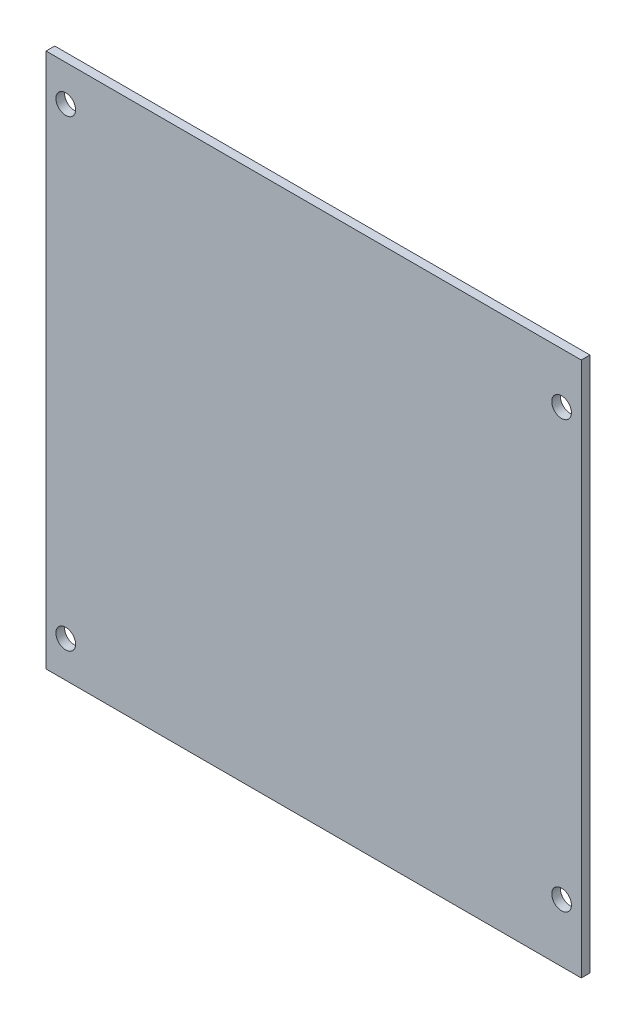
SolidWorks part; units mm, degrees
material "FR4"
ref_plane "Front Plane" through (0, 0, 0) normal (0, 0, 1) x (1, 0, 0)
ref_plane "Top Plane" through (0, 0, 0) normal (0, 1, 0) x (1, 0, 0)
ref_plane "Right Plane" through (0, 0, 0) normal (1, 0, 0) x (0, 0, -1)
sketch "Sketch1" plane through (0, 0, 0) normal (0, 0, 1) x (1, 0, 0)
  line L1 (46.25, -46.25) -> (-46.25, -46.25)
  line L2 (46.25, -46.25) -> (46.25, 46.25)
  line L3 (46.25, 46.25) -> (-46.25, 46.25)
  line L4 (-46.25, -46.25) -> (-46.25, 46.25)
  line L5 (46.25, -46.25) -> (-46.25, 46.25) construction
  line L6 (46.25, 46.25) -> (-46.25, -46.25) construction
  point P0 (0, 0)
  dimension "D1" = 92.5
  dimension "D2" = 92.5
extrude "Boss-Extrude1" add sketch "Sketch1" along normal blind 1.5
ref_plane "Plane1" through (0, 0, 0) normal (0, 1, 0) x (1, 0, 0)
ref_plane "Plane2" through (0, 0, 0) normal (1, 0, 0) x (0, 0, -1)
sketch "Sketch5" plane through (0, 0, 1.5) normal (0, 0, 1) x (1, 0, 0)
  line L0 (42.85, -36.2) -> (42.85, 37.5) construction
  line L1 (-42.85, -40) -> (-42.85, 40) construction
  line L2 (-42.85, 40) -> (42.85, 40) construction
  line L3 (42.85, 40) -> (42.85, 37.5) construction
  line L4 (-42.85, -40) -> (42.85, -40) construction
  line L5 (42.85, -40) -> (42.85, -36.2) construction
  line L6 (42.85, 40) -> (-42.85, -40) construction
  line L7 (46.25, -46.25) -> (46.25, 46.25) construction
  point P4 (0, 0)
sketch_block_instance "Block1-1"
sketch_block "Block2"
hole_wizard "M3 Clearance Hole1" positions "3DSketch1" profile "Sketch6" hole size "M3" standard "ISO" end condition through all
sketch3d "3DSketch1"
  point P0 (42.85, -36.2, 1.5)
  point P3 (42.85, 37.5, 1.5)
  point P6 (-42.85, 40, 1.5)
  point P9 (-42.85, -40, 1.5)
sketch "Sketch6" plane through (42.85, -36.2, 1.5) normal (1, 0, 0) x (0, -1, 0)
  line L0 (0, 0) -> (0, 1.5)
  line L1 (0, 1.5) -> (1.7, 1.5)
  line L2 (1.7, 1.5) -> (1.7, 0)
  line L5 (1.7, 0) -> (0, 0)
  line L11 (0, -6.35) -> (0, 107.95) construction
  dimension "Thru Hole Dia." = 3.4
  dimension "Thru Hole Depth" = 1.5
